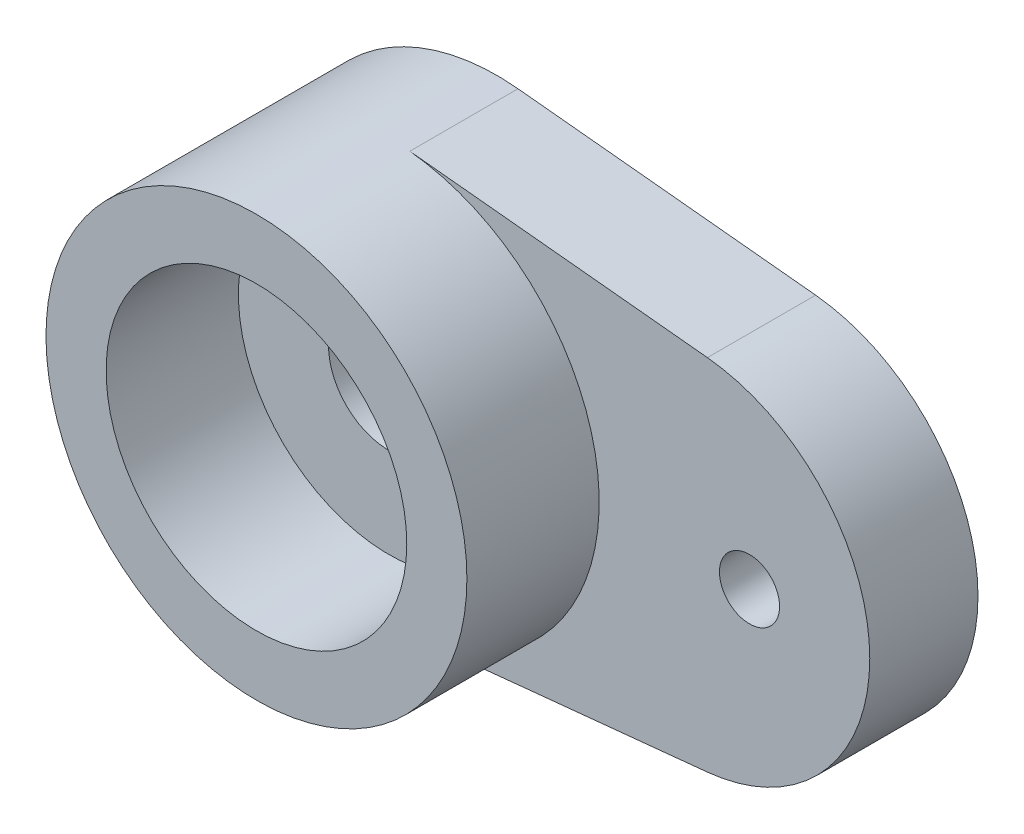
SolidWorks part; units mm, degrees
ref_plane "Front Plane" through (0, 0, 0) normal (0, 0, 1) x (1, 0, 0)
ref_plane "Top Plane" through (0, 0, 0) normal (0, 1, 0) x (1, 0, 0)
ref_plane "Right Plane" through (0, 0, 0) normal (1, 0, 0) x (0, 0, -1)
sketch "Sketch1" plane through (0, 0, 0) normal (0, 0, 1) x (1, 0, 0)
  line L0 (-1.2713, 15.991) -> (407.0098, 31.3902) construction
  line L1 (0.35, 3.4825) -> (5.3, 2.985)
  line L2 (5.3, -2.985) -> (0.35, -3.4825)
  arc A0 (0.35, 3.4825) -> (0.35, -3.4825) centre (0, 0) ccw
  arc A1 (5.3, 2.985) -> (5.3, -2.985) centre (5, 0) cw
  circle A2 centre (0, 0) radius 1
  circle A3 centre (6, 0) radius 0.5
  dimension "D1" = 1
  dimension "D4" = 2
  dimension "D5" = 3
  dimension "D3" = 3.5
  dimension "D2" = 6
  dimension "D6" = 5
extrude "Boss-Extrude3" add sketch "Sketch1" along normal blind 1.8 contours A0 L2 A1 L1
sketch "Sketch4" plane through (0, 0, 1.8) normal (0, 0, 1) x (1, 0, 0)
  circle A0 centre (0, 0) radius 2.5
  circle A1 centre (0, 0) radius 3.5
  dimension "D1" = 5
  dimension "D2" = 7
extrude "Boss-Extrude4" add sketch "Sketch4" along normal blind 2.2
